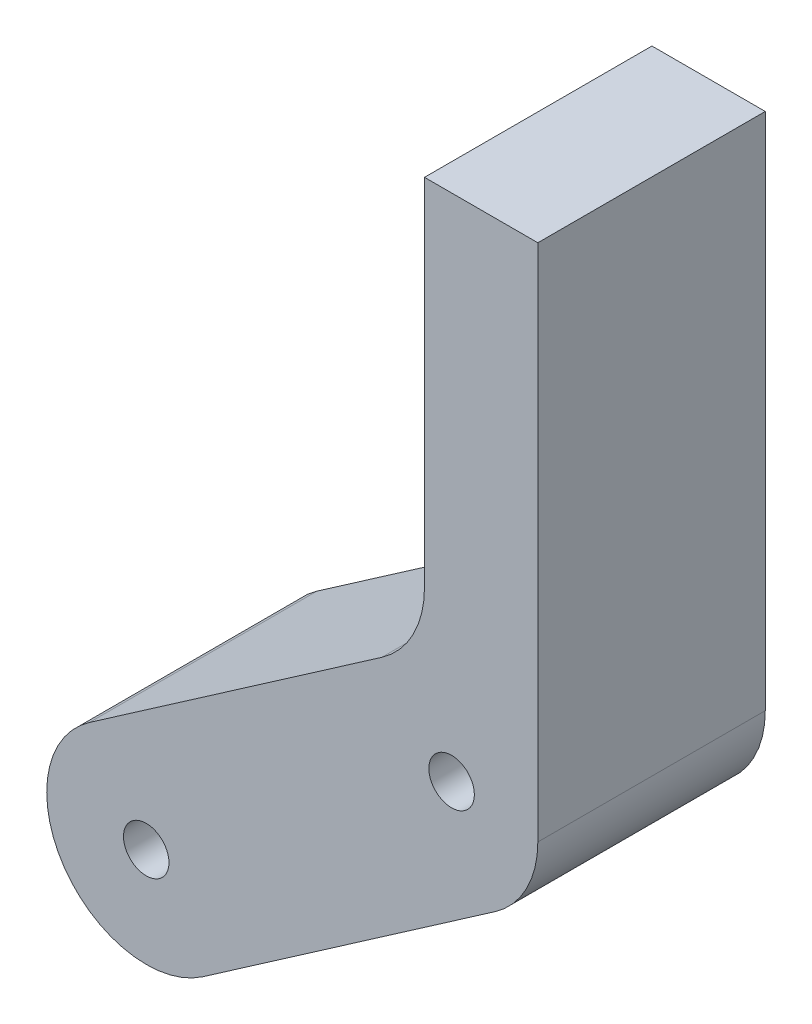
SolidWorks part; units mm, degrees
ref_plane "Front Plane" through (0, 0, 0) normal (0, 0, 1) x (1, 0, 0)
ref_plane "Top Plane" through (0, 0, 0) normal (0, 1, 0) x (1, 0, 0)
ref_plane "Right Plane" through (0, 0, 0) normal (1, 0, 0) x (0, 0, -1)
other "Configuration Table"
ref_plane "基准面1" through (0, 0, 11) normal (0, 0, 1) x (1, 0, 0)
sketch "草图1" plane through (0, 0, 11) normal (0, 0, 1) x (1, 0, 0)
  line L0 (22.2422, 32.4363) -> (14.2688, 32.4363)
  line L1 (14.2688, 32.4363) -> (14.2688, 3.7703)
  line L2 (14.2688, 3.7703) -> (-9.2938, -12.5558)
  line L3 (-1.3204, -24.0634) -> (22.2422, -7.7373)
  line L4 (22.2422, -7.7373) -> (22.2422, 32.4363)
  arc A0 (-9.2938, -12.5558) -> (-1.3204, -24.0634) centre (-5.3071, -18.3096) ccw
extrude "凸台-拉伸1" add sketch "草图1" against normal blind 22
sketch "草图2" plane through (0, 0, -11) normal (0, 0, -1) x (-1, 0, 0)
  line L0 (6.652, -14.5424) -> (-11.3739, -8.1069)
  line L1 (-11.3739, -8.1069) -> (-11.8782, -9.5196)
  line L2 (-11.8782, -9.5196) -> (3.207, -14.9052)
  line L3 (3.029, -21.5974) -> (1.3204, -24.0634)
  line L4 (12.3071, -18.3096) -> (9.3071, -18.3096)
  arc A0 (3.207, -14.9052) -> (3.029, -21.5974) centre (5.3071, -18.3096) ccw
  arc A1 (1.3204, -24.0634) -> (12.3071, -18.3096) centre (5.3071, -18.3096) ccw
  arc A2 (9.3071, -18.3096) -> (6.652, -14.5424) centre (5.3071, -18.3096) ccw
extrude "切除-拉伸1" cut sketch "草图2" against normal blind 4
sketch "草图3" plane through (7.5209, 2.6851, 0) normal (-0.9418, -0.3362, 0) x (0, 0, 1)
  line L0 (-9, -12.9592) -> (-7, -12.9592)
  line L1 (-7, -12.9592) -> (-7, -11.4592)
  line L2 (-7, -11.4592) -> (-9, -11.4592)
  line L3 (-9, -11.4592) -> (-9, -12.9592)
extrude "切除-拉伸2" cut sketch "草图3" against normal blind 5
fillet "圆角1" radius 7 2 edges at (14.2688, 3.7703, 0) (22.2422, -7.7373, 0)
sketch "草图11" plane through (10.8366, -15.64, 0) normal (0.5695, -0.822, 0) x (0.822, 0.5695, 0)
  line L0 (15.9637, -11) -> (36.7558, -11) construction
  line L1 (-24.1705, 15.7519) -> (50.6958, 15.7519)
  line L2 (-24.1705, 15.7519) -> (-24.1705, 5)
  line L3 (-24.1705, 5) -> (50.6958, 5)
  line L4 (50.6958, 15.7519) -> (50.6958, 5)
  dimension "D1" = 16
extrude "切除-拉伸3" cut sketch "草图11" against normal through all both and the other way through all
sketch "草图12" plane through (0, 0, 5) normal (0, 0, 1) x (1, 0, 0)
  line L0 (16.175, -3.425) -> (-5.3071, -18.3096)
  line L1 (-1.3204, -24.0634) -> (19.2289, -9.8251) construction
  circle A0 centre (-5.3071, -18.3096) radius 1.6
  circle A1 centre (16.175, -3.425) radius 1.6
  dimension "D1" = 3.2
  dimension "D2" = 3.2
extrude "切除-拉伸4" cut sketch "草图12" against normal through all both and the other way through all
